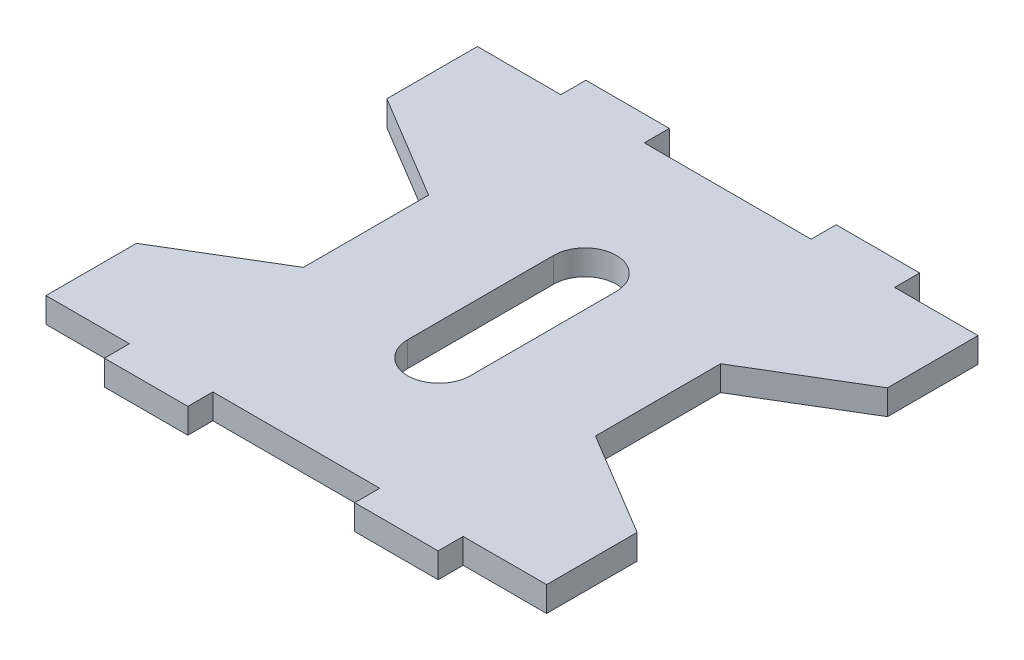
SolidWorks part; units mm, degrees
ref_plane "前视基准面" through (0, 0, 0) normal (0, 0, 1) x (1, 0, 0)
ref_plane "上视基准面" through (0, 0, 0) normal (0, 1, 0) x (1, 0, 0)
ref_plane "右视基准面" through (0, 0, 0) normal (1, 0, 0) x (0, 0, -1)
sketch "草图2" plane through (0, 0, 0) normal (0, 1, 0) x (1, 0, 0)
  line L0 (43.4232, 0) -> (-43.4232, 0) construction
  line L1 (0, 25.8962) -> (0, -25.8962) construction
  line L2 (17.5, -7.5) -> (17.5, 7.5)
  line L3 (17.5, 7.5) -> (30, 15)
  line L4 (30, 15) -> (30, 25.85)
  line L5 (30, 25.85) -> (20, 25.85)
  line L6 (20, 25.85) -> (20, 28.85)
  line L7 (20, 28.85) -> (10, 28.85)
  line L8 (10, 28.85) -> (10, 25.85)
  line L9 (10, 25.85) -> (-10, 25.85)
  line L10 (-10, 28.85) -> (-10, 25.85)
  line L11 (-20, 28.85) -> (-10, 28.85)
  line L12 (-20, 25.85) -> (-20, 28.85)
  line L13 (-30, 25.85) -> (-20, 25.85)
  line L14 (-30, 15) -> (-30, 25.85)
  line L15 (-17.5, 7.5) -> (-30, 15)
  line L16 (-17.5, -7.5) -> (-17.5, 7.5)
  line L17 (-17.5, -7.5) -> (-30, -15)
  line L18 (-30, -15) -> (-30, -25.85)
  line L19 (-30, -25.85) -> (-20, -25.85)
  line L20 (-20, -25.85) -> (-20, -28.85)
  line L21 (-20, -28.85) -> (-10, -28.85)
  line L22 (-10, -28.85) -> (-10, -25.85)
  line L23 (10, -25.85) -> (-10, -25.85)
  line L24 (10, -28.85) -> (10, -25.85)
  line L25 (20, -28.85) -> (10, -28.85)
  line L26 (20, -25.85) -> (20, -28.85)
  line L27 (30, -25.85) -> (20, -25.85)
  line L28 (30, -15) -> (30, -25.85)
  line L29 (17.5, -7.5) -> (30, -15)
  line L30 (-3.75, 8.75) -> (-3.75, -8.75)
  line L31 (3.75, 8.75) -> (3.75, -8.75)
  arc A0 (3.75, 8.75) -> (-3.75, 8.75) centre (0, 8.75) ccw
  arc A1 (3.75, -8.75) -> (-3.75, -8.75) centre (0, -8.75) cw
  point P0 (0, -25.85)
  point P4 (0, 0)
  point P8 (0, 0)
  point P17 (0, 25.85)
  point P25 (-17.5, 0)
  point P38 (17.5, 0)
  point P44 (-3.75, 0)
  point P47 (3.75, 0)
  dimension "D1" = 7.5
  dimension "D2" = 10.85
  dimension "D3" = 3
  dimension "D4" = 60
  dimension "D5" = 51.7
  dimension "D6" = 3
  dimension "D7" = 10
  dimension "D8" = 10
  dimension "D9" = 12.5
  dimension "D10" = 17.5
  dimension "D11" = 3.75
extrude "凸台-拉伸1" add sketch "草图2" along normal blind 3
